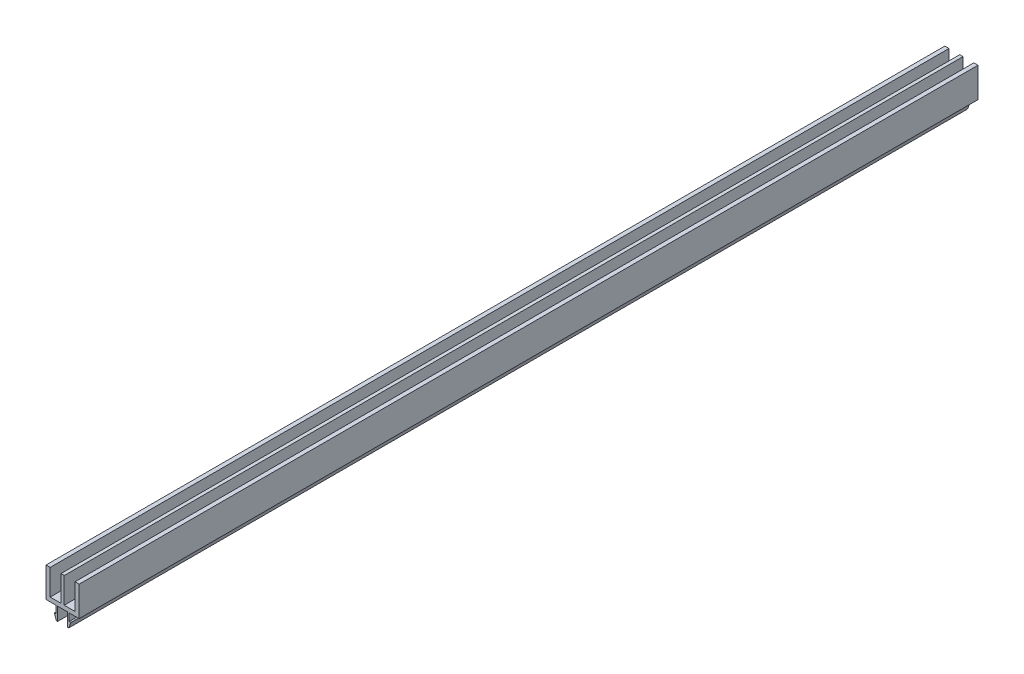
SolidWorks part; units mm, degrees
ref_plane "Plan de face" through (0, 0, 0) normal (0, 0, 1) x (1, 0, 0)
ref_plane "Plan de dessus" through (0, 0, 0) normal (0, 1, 0) x (1, 0, 0)
ref_plane "Plan de droite" through (0, 0, 0) normal (1, 0, 0) x (0, 0, -1)
ref_plane "Plan1" through (0, 0, 50) normal (0, 0, 1) x (1, 0, 0)
sketch "Esquisse1" plane through (0, 0, 50) normal (0, 0, 1) x (1, 0, 0)
  line L0 (-1, 2.5) -> (-7.5, 2.5)
  line L1 (-7.5, 2.5) -> (-7.5, 18)
  line L2 (-7.5, 18) -> (-10, 18)
  line L3 (-10, 18) -> (-10, 0)
  line L4 (-10, 0) -> (-4, 0)
  line L5 (-4, 0) -> (-4, -4.5)
  line L6 (-4, -4.5) -> (-5, -4.5)
  line L7 (-5, -4.5) -> (-3.75, -8)
  line L8 (-3.75, -8) -> (-3, -8)
  line L9 (-3, -8) -> (-3, 0)
  line L10 (-3, 0) -> (3, 0)
  line L11 (3, 0) -> (3, -8)
  line L12 (3, -8) -> (3.75, -8)
  line L13 (3.75, -8) -> (5, -4.5)
  line L14 (5, -4.5) -> (4, -4.5)
  line L15 (4, -4.5) -> (4, 0)
  line L16 (4, 0) -> (10, 0)
  line L17 (10, 0) -> (10, 18)
  line L18 (10, 18) -> (7.5, 18)
  line L19 (7.5, 18) -> (7.5, 2.5)
  line L20 (7.5, 2.5) -> (1, 2.5)
  line L21 (1, 2.5) -> (1, 18)
  line L22 (1, 18) -> (-1, 18)
  line L23 (-1, 18) -> (-1, 2.5)
extrude "Boss.-Extru.1" add sketch "Esquisse1" against normal blind 542
